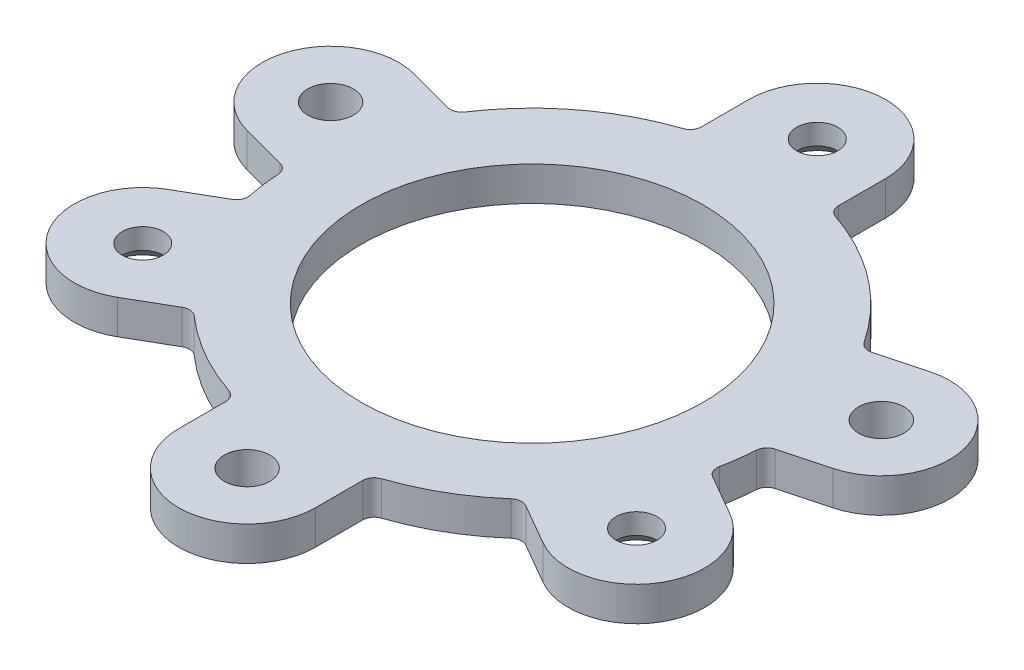
SolidWorks part; units mm, degrees
material "Delrin 2700 NC010, Low Viscosity Acetal Copolymer (SS)"
ref_plane "Front" through (0, 0, 0) normal (0, 0, 1) x (1, 0, 0)
ref_plane "Top" through (0, 0, 0) normal (0, 1, 0) x (1, 0, 0)
ref_plane "Right" through (0, 0, 0) normal (1, 0, 0) x (0, 0, -1)
sketch "Sketch1" plane through (0, 0, 0) normal (0, 1, 0) x (1, 0, 0)
  line L0 (-3, 0) -> (3, 0) construction
  line L5 (0, 0) -> (0, -12.5) construction
  line L8 (3, 0) -> (3, -12.5)
  line L9 (-3, 0) -> (-3, -12.5)
  line L12 (0, 0) -> (0, 12.5) construction
  line L25 (0, 0) -> (10.8253, -6.25) construction
  line L28 (-3, 0) -> (-3, 12.5)
  line L29 (3, 0) -> (3, 12.5)
  line L30 (1.5, 2.5981) -> (12.3253, -3.6519)
  line L31 (-1.5, -2.5981) -> (9.3253, -8.8481)
  line L32 (0, 0) -> (-10.8253, -6.25) construction
  line L33 (1.5, -2.5981) -> (-9.3253, -8.8481)
  line L34 (-1.5, 2.5981) -> (-12.3253, -3.6519)
  line L35 (0, 0) -> (-12.0741, 3.2352) construction
  line L38 (0, 22.4638) -> (0, -22.4638) construction
  line L39 (-0.7765, -2.8978) -> (-12.8505, 0.3375)
  line L40 (0.7765, 2.8978) -> (-11.2976, 6.133)
  line L41 (0.7765, -2.8978) -> (12.8505, 0.3375)
  line L42 (-0.7765, 2.8978) -> (11.2976, 6.133)
  line L43 (0, 0) -> (12.0741, 3.2352) construction
  line L44 (0, 0) -> (-3, 0) construction
  line L45 (0, 0) -> (0.7765, -2.8978) construction
  circle A1 centre (0, 0) radius 7.5
  arc A11 (3, 0) -> (-3, 0) centre (0, 0) ccw
  arc A12 (-3, -12.5) -> (3, -12.5) centre (0, -12.5) ccw
  circle A13 centre (0, -12.5) radius 1
  circle A21 centre (0, 0) radius 10.5
  arc A38 (-3, 0) -> (3, 0) centre (0, 0) ccw
  arc A39 (3, 12.5) -> (-3, 12.5) centre (0, 12.5) ccw
  circle A40 centre (0, 12.5) radius 0.9
  circle A41 centre (0, 0) radius 10.5
  circle A42 centre (10.8253, -6.25) radius 0.9
  arc A43 (1.5, 2.5981) -> (-1.5, -2.5981) centre (0, 0) ccw
  arc A44 (9.3253, -8.8481) -> (12.3253, -3.6519) centre (10.8253, -6.25) ccw
  circle A45 centre (0, 0) radius 10.5
  circle A46 centre (-10.8253, -6.25) radius 0.9
  arc A47 (1.5, -2.5981) -> (-1.5, 2.5981) centre (0, 0) ccw
  arc A48 (-12.3253, -3.6519) -> (-9.3253, -8.8481) centre (-10.8253, -6.25) ccw
  circle A49 centre (-12.0741, 3.2352) radius 1
  arc A50 (-0.7765, -2.8978) -> (0.7765, 2.8978) centre (0, 0) ccw
  arc A51 (-11.2976, 6.133) -> (-12.8505, 0.3375) centre (-12.0741, 3.2352) ccw
  arc A52 (-0.7765, 2.8978) -> (0.7765, -2.8978) centre (0, 0) ccw
  arc A53 (12.8505, 0.3375) -> (11.2976, 6.133) centre (12.0741, 3.2352) ccw
  circle A54 centre (12.0741, 3.2352) radius 1
  point P2 (0, 6.25)
  point P10 (0, -6.25)
  point P21 (5.4127, -3.125)
  point P22 (-6.037, 1.6176)
  point P23 (6.037, 1.6176)
  point P25 (-5.4127, -3.125)
  point P35 (-5.4127, -3.125)
  point P38 (-5.4127, 3.125)
  point P52 (0, 0)
  point P71 (-5.4127, -3.125)
  point P78 (-5.4127, 3.125)
  dimension "D1" = 1.8
  dimension "D2" = 15
  dimension "D3" = 3
  dimension "D5" = 21
  dimension "D6" = 3
  dimension "D7" = 2
  dimension "D4" = 2
  dimension "D8" = 12.5
  dimension "D9" = 2
  dimension "D10" = 105
extrude "Boss-Extrude1" add sketch "Sketch1" along normal blind 1.5
fillet "Fillet1" radius 0.5 12 edges at (-7.2142, 0.75, 7.6292) (-10.2142, 0.75, 2.4331) (-10.4959, 0.75, 0.2935) (-8.943, 0.75, -5.5021) (-3, 0.75, -10.0623) (3, 0.75, -10.0623) (8.943, 0.75, -5.5021) (10.4959, 0.75, 0.2935) (10.2142, 0.75, 2.4331) (7.2142, 0.75, 7.6292) (3, 0.75, 10.0623) (-3, 0.75, 10.0623)
chamfer "Chamfer1" distance 0.6 angle 45 3 edges at (10.8253, 0, 7.15) (0, 0, -11.6) (-10.8253, 0, 7.15)
equation "\"PostAngle\"=75"
